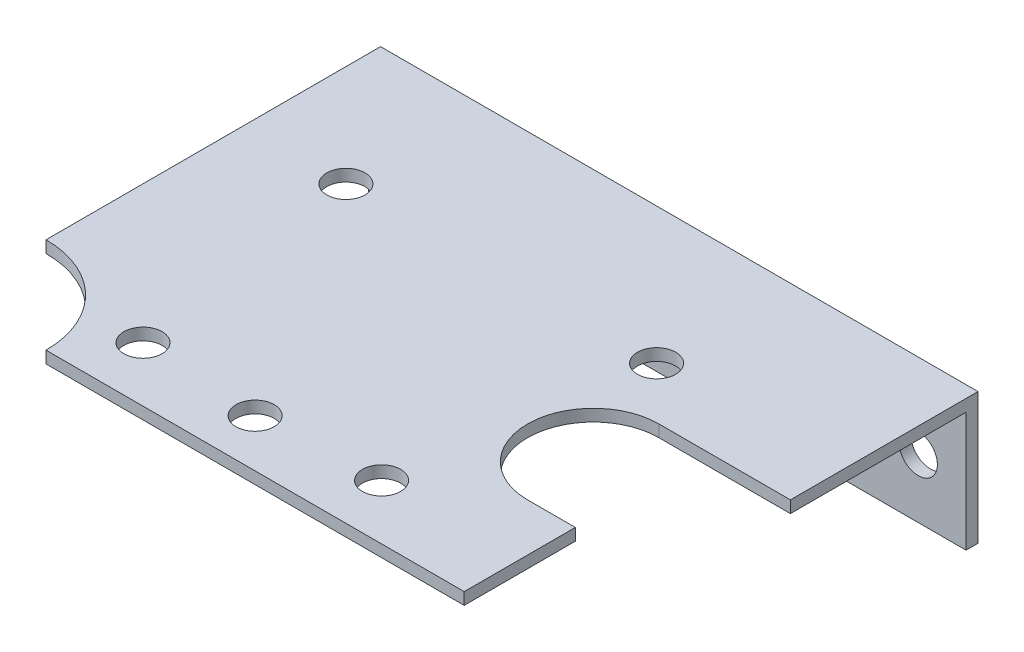
SolidWorks part; units mm, degrees
ref_plane "前视基准面" through (0, 0, 0) normal (0, 0, 1) x (1, 0, 0)
ref_plane "上视基准面" through (0, 0, 0) normal (0, 1, 0) x (1, 0, 0)
ref_plane "右视基准面" through (0, 0, 0) normal (1, 0, 0) x (0, 0, -1)
sketch "草图1" plane through (0, 0, 0) normal (0, 1, 0) x (1, 0, 0)
  line L0 (21.5, 35) -> (21.5, 0) construction
  line L1 (8, 0) -> (43, 0)
  line L2 (0, 8) -> (0, 36)
  line L3 (0, 36) -> (50, 36)
  line L4 (43, 0) -> (43, 9.3)
  line L5 (78.2626, 14.8) -> (-19.7659, 14.8) construction
  line L6 (39, 20.3) -> (50, 20.3)
  line L7 (39, 9.3) -> (43, 9.3)
  line L8 (50, 20.3) -> (50, 36)
  circle A0 centre (8.5, 24.6) radius 1.6
  circle A2 centre (21.5, 4) radius 1.6
  circle A3 centre (34.5, 24.6) radius 1.6
  arc A4 (39, 9.3) -> (39, 20.3) centre (39, 14.8) cw
  circle A5 centre (31.482, 4.6) radius 1.6
  circle A6 centre (11.518, 4.6) radius 1.6
  arc A7 (8, 0) -> (0, 8) centre (0, 0) ccw
  dimension "D3" = 3.2
  dimension "D4" = 26
  dimension "D5" = 20.6
  dimension "D6" = 11.4
  dimension "D8" = 5.5
  dimension "D10" = 3.2
  dimension "D11" = 20
  dimension "D7" = 10.8
  dimension "D16" = 8
  dimension "D1" = 50
  dimension "D2" = 36
  dimension "D9" = 4
  dimension "D12" = 10
  dimension "D13" = 4
  dimension "D14" = 21.5
  dimension "D15" = 43
extrude "凸台-拉伸1" add sketch "草图1" along normal blind 1
sketch "草图2" plane through (0, 1, 0) normal (0, 1, 0) x (1, 0, 0)
  line L0 (50, 20.3) -> (50, 36) construction
  line L1 (0, 36) -> (50, 36)
  line L2 (0, 36) -> (0, 35)
  line L3 (0, 35) -> (50, 35)
  line L4 (50, 36) -> (50, 35)
  dimension "D1" = 1
extrude "凸台-拉伸2" add sketch "草图2" against normal blind 11
sketch "草图3" plane through (0, 0, -35) normal (0, 0, 1) x (1, 0, 0)
  line L0 (50, -10) -> (50, 0) construction
  line L2 (0, -10) -> (50, -10) construction
  circle A0 centre (46, -5) radius 1.6
  circle A1 centre (18, -5) radius 1.6
  dimension "D1" = 3.2
  dimension "D2" = 3.2
  dimension "D3" = 4
  dimension "D4" = 5
  dimension "D5" = 28
extrude "切除-拉伸1" cut sketch "草图3" against normal blind 10
